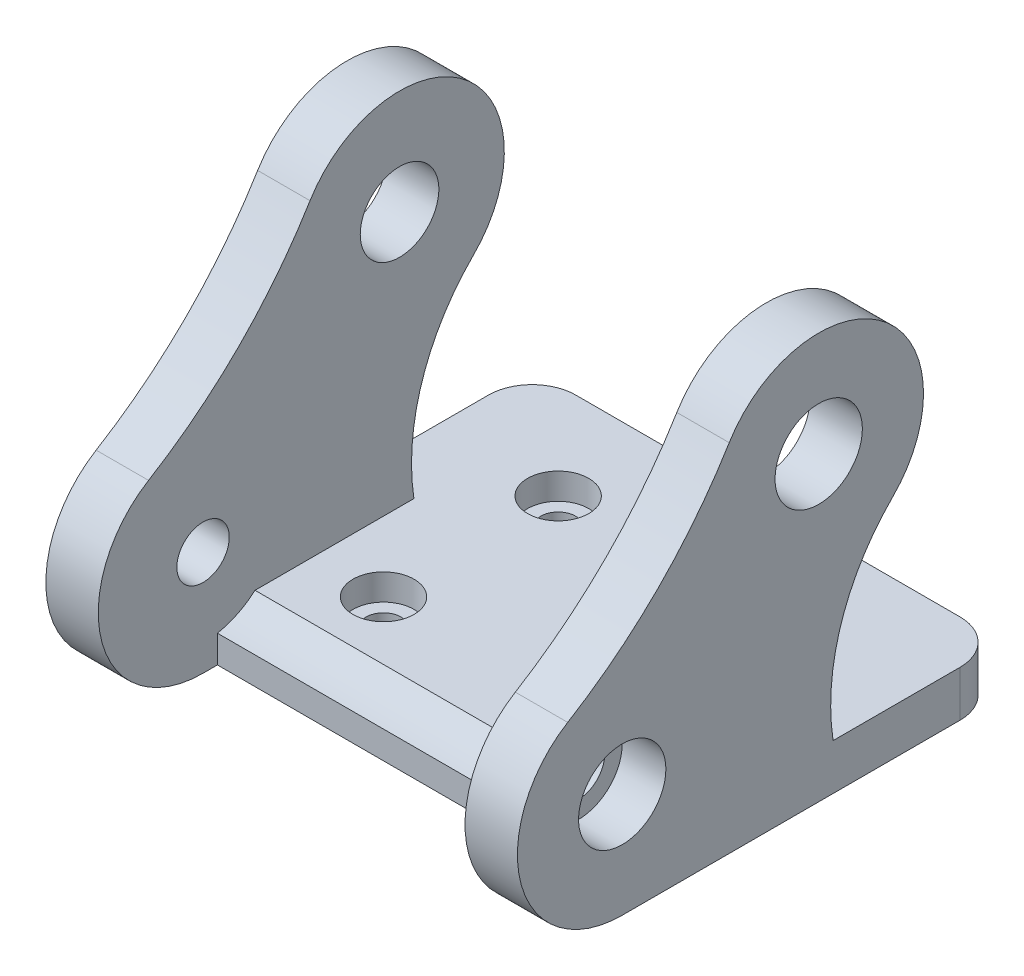
SolidWorks part; units mm, degrees
ref_plane "前视基准面" through (0, 0, 0) normal (0, 0, 1) x (1, 0, 0)
ref_plane "上视基准面" through (0, 0, 0) normal (0, 1, 0) x (1, 0, 0)
ref_plane "右视基准面" through (0, 0, 0) normal (1, 0, 0) x (0, 0, -1)
other "Configuration Table"
sketch "草图1" plane through (0, 0, 0) normal (1, 0, 0) x (0, 0, -1)
  line L0 (-15, -23) -> (14.1216, -23)
  line L1 (14.1216, -23) -> (14.1216, -19.5)
  line L2 (0, 0) -> (0, -15) construction
  line L3 (0, -15) -> (-15, -15) construction
  line L4 (-15, -15) -> (0, 0) construction
  line L5 (14.1216, -19.5) -> (1.0971, -19.5)
  circle A0 centre (0, 0) radius 8
  arc A1 (-19.161, -8.1673) -> (-6.8327, 4.161) centre (-38.3623, 23.3623) ccw
  circle A2 centre (-15, -15) radius 8
  arc A3 (5.6501, -5.6636) -> (1.0971, -19.5) centre (17.0371, -17.0779) ccw
  dimension "D1" = 16
  dimension "D2" = 16
  dimension "D3" = 15
  dimension "D4" = 15
  dimension "D5" = 3.5
extrude "凸台-拉伸1" add sketch "草图1" along normal blind 4
sketch "草图7" plane through (4, 0, 0) normal (1, 0, 0) x (0, 0, -1)
  circle A0 centre (0, 0) radius 3.3333
  dimension "D1" = 6.6667
extrude "切除-拉伸3" cut sketch "草图7" against normal through all
sketch "草图8" plane through (4, 0, 0) normal (1, 0, 0) x (0, 0, -1)
  circle A0 centre (-15, -15) radius 2
  dimension "D1" = 4
extrude "切除-拉伸4" cut sketch "草图8" against normal through all
sketch "草图9" plane through (0, 0, 0) normal (-1, 0, 0) x (0, 0, 1)
  line L3 (-1.0971, -19.5) -> (-14.1216, -19.5)
  line L4 (-14.1216, -19.5) -> (-14.1216, -23)
  line L5 (-14.1216, -23) -> (15, -23)
  line L6 (-1.0971, -19.5) -> (-14.1216, -19.5)
  line L7 (-14.1216, -19.5) -> (-14.1216, -23)
  line L8 (-14.1216, -23) -> (15, -23)
  circle A0 centre (0, 0) radius 3
  circle A1 centre (15, -15) radius 2
  arc A4 (-1.0971, -19.5) -> (-5.6501, -5.6636) centre (-17.0371, -17.0779) ccw
  arc A5 (15, -23) -> (19.161, -8.1673) centre (15, -15) ccw
  arc A6 (6.8327, 4.161) -> (19.161, -8.1673) centre (38.3623, 23.3623) ccw
  arc A7 (6.8327, 4.161) -> (-5.6501, -5.6636) centre (0, 0) ccw
  arc A8 (-1.0971, -19.5) -> (-5.6501, -5.6636) centre (-17.0371, -17.0779) ccw
  arc A9 (15, -23) -> (19.161, -8.1673) centre (15, -15) ccw
  arc A10 (6.8327, 4.161) -> (19.161, -8.1673) centre (38.3623, 23.3623) ccw
  arc A11 (6.8327, 4.161) -> (-5.6501, -5.6636) centre (0, 0) ccw
  dimension "D2" = 4
  dimension "D3" = 6
  dimension "D1" = 0
extrude "凸台-拉伸2" add sketch "草图9" along normal blind 4 from offset 28 separate body
sketch "草图10" plane through (0, 0, 0) normal (-1, 0, 0) x (0, 0, 1)
  line L0 (-1.0971, -19.5) -> (-14.1216, -19.5)
  line L1 (-14.1216, -19.5) -> (-14.1216, -23)
  line L2 (-14.1216, -23) -> (-1.0971, -23)
  line L3 (-14.1216, -23) -> (15, -23) construction
  line L4 (-1.0971, -23) -> (-1.0971, -19.5)
extrude "凸台-拉伸3" add sketch "草图10" along normal up to next
sketch "草图11" plane through (0, 0, -1.0971) normal (0, 0, 1) x (1, 0, 0)
  line L4 (-28, -19.5) -> (-28, -23)
  line L5 (-28, -23) -> (0, -23)
  line L6 (0, -23) -> (0, -19.5)
  line L7 (0, -19.5) -> (-28, -19.5)
  line L8 (-28, -19.5) -> (-28, -23)
  line L9 (-28, -23) -> (0, -23)
  line L10 (0, -23) -> (0, -19.5)
  line L11 (0, -19.5) -> (-28, -19.5)
  dimension "D1" = 0
extrude "凸台-拉伸4" add sketch "草图11" along normal blind 15
scale "缩放比例1" scale about centroid uniform scaling yes scale factor 1.5
sketch "草图13" plane through (-34.9722, 0, 0) normal (1, 0, 0) x (0, 0, -1)
  line L1 (-19.0045, -22.088) -> (3.4955, -22.088) construction
  line L2 (-19.0045, -27.338) -> (-19.0045, -22.088) construction
  line L3 (-14.6972, -22.088) -> (-19.0045, -22.088)
  line L4 (-19.0045, -22.088) -> (-19.0045, -24.1862)
  arc A0 (-14.6972, -22.088) -> (-19.0045, -24.1862) centre (-20.6502, -15.338) cw
  dimension "D1" = 9
extrude "切除-拉伸5" cut sketch "草图13" along normal up to surface (42 mm away) up to face at (7.0278, -15.338, 17.6502)
sketch "草图15" plane through (0, 0, 19.0045) normal (0, 0, 1) x (1, 0, 0)
  line L4 (7.0278, -27.338) -> (7.0278, -24.1862)
  line L5 (7.0278, -24.1862) -> (-34.9722, -24.1862)
  line L6 (-34.9722, -24.1862) -> (-34.9722, -27.338)
  line L7 (-34.9722, -27.338) -> (7.0278, -27.338)
  line L8 (7.0278, -27.338) -> (7.0278, -24.1862)
  line L9 (7.0278, -24.1862) -> (-34.9722, -24.1862)
  line L10 (-34.9722, -24.1862) -> (-34.9722, -27.338)
  line L11 (-34.9722, -27.338) -> (7.0278, -27.338)
  dimension "D1" = 0
sketch "草图17" plane through (-40.9722, 0, 0) normal (-1, 0, 0) x (0, 0, 1)
  circle A0 centre (20.6502, -15.338) radius 6
  dimension "D1" = 12
extrude "切除-拉伸6" cut sketch "草图17" against normal blind 1.4
sketch "草图18" plane through (13.0278, 0, 0) normal (1, 0, 0) x (0, 0, -1)
  circle A0 centre (-20.6502, -15.338) radius 5
  dimension "D1" = 10
extrude "切除-拉伸7" cut sketch "草图18" against normal blind 5
sketch "草图19" plane through (0, -27.338, 0) normal (0, -1, 0) x (1, 0, 0)
  line L1 (-0.9722, -12.0138) -> (-26.9722, -12.0138)
  line L2 (-0.9722, -12.0138) -> (-0.9722, 7.9862)
  line L3 (-0.9722, 7.9862) -> (-26.9722, 7.9862)
  line L4 (-26.9722, -12.0138) -> (-26.9722, 7.9862)
  line L5 (-0.9722, -12.0138) -> (-26.9722, 7.9862) construction
  line L6 (-0.9722, 7.9862) -> (-26.9722, -12.0138) construction
  line L11 (13.0278, -23.0322) -> (-40.9722, 19.0045) construction
  line L12 (-40.9722, -23.0322) -> (-40.9722, 20.6502) construction
  line L13 (7.0278, 19.0045) -> (-34.9722, 19.0045) construction
  line L14 (-40.9722, -23.0322) -> (13.0278, 19.0045) construction
  line L15 (13.0278, 20.6502) -> (13.0278, -23.0322) construction
  circle A0 centre (-0.9722, -12.0138) radius 2
  circle A1 centre (-26.9722, -12.0138) radius 2
  circle A2 centre (-26.9722, 7.9862) radius 2
  circle A3 centre (-0.9722, 7.9862) radius 2
  point P0 (-13.9722, -2.0138)
  point P6 (-13.9722, -2.0138)
  dimension "D1" = 26
  dimension "D2" = 4
  dimension "D4" = 4
  dimension "D5" = 4
  dimension "D6" = 4
  dimension "D3" = 20
extrude "切除-拉伸8" cut sketch "草图19" against normal up to next and the other way through all contours A0 | A1 | A2 | A3
fillet "圆角1" radius 5 2 edges at (13.0278, -24.713, -23.0322) (-40.9722, -24.713, -23.0322)
sketch "草图21" plane through (0, -22.088, 0) normal (0, 1, 0) x (1, 0, 0)
  circle A0 centre (-26.9722, 12.0138) radius 3.5
  circle A1 centre (-0.9722, 12.0138) radius 3.5
  circle A2 centre (-0.9722, -7.9862) radius 3.5
  circle A3 centre (-26.9722, -7.9862) radius 3.5
  dimension "D1" = 7
  dimension "D2" = 7
  dimension "D3" = 7
  dimension "D4" = 7
extrude "切除-拉伸9" cut sketch "草图21" against normal blind 3
